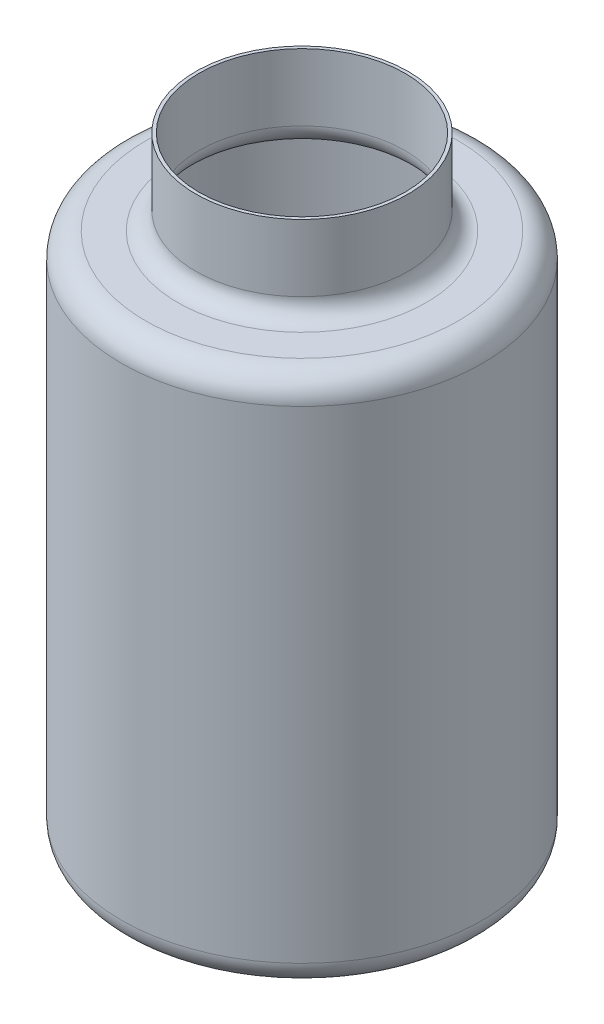
SolidWorks part; units mm, degrees
ref_plane "Front Plane" through (0, 0, 0) normal (0, 0, 1) x (1, 0, 0)
ref_plane "Top Plane" through (0, 0, 0) normal (0, 1, 0) x (1, 0, 0)
ref_plane "Right Plane" through (0, 0, 0) normal (1, 0, 0) x (0, 0, -1)
sketch "Sketch2" plane through (0, 0, 0) normal (0, 0, 1) x (1, 0, 0)
  line L1 (0, 151.638) -> (19.558, 151.638) construction
  line L2 (24.638, 146.558) -> (24.638, 130.556)
  line L3 (29.718, 125.476) -> (37.338, 125.476)
  line L4 (42.418, 120.396) -> (42.418, 5.08)
  line L5 (37.338, 0) -> (0, 0)
  line L6 (0, -97.3781) -> (0, 179.0981) construction
  line L7 (0, 152.4) -> (19.558, 152.4) construction
  line L8 (25.4, 146.558) -> (25.4, 130.556)
  line L9 (29.718, 126.238) -> (37.338, 126.238)
  line L10 (43.18, 120.396) -> (43.18, 5.08)
  line L11 (37.338, -0.762) -> (0, -0.762)
  line L12 (-0.762, 152.4) -> (19.558, 152.4) construction
  line L13 (-0.762, -0.762) -> (-0.762, 152.4) construction
  line L14 (37.338, -0.762) -> (-0.762, -0.762) construction
  line L15 (0, 0) -> (0, 151.638) construction
  line L16 (0, -0.762) -> (0, 0)
  line L17 (0, 152.4) -> (0, 151.638) construction
  line L18 (25.4, 146.558) -> (24.638, 146.558)
  arc A0 (42.418, 5.08) -> (37.338, 0) centre (37.338, 5.08) cw
  arc A1 (37.338, 125.476) -> (42.418, 120.396) centre (37.338, 120.396) cw
  arc A2 (24.638, 130.556) -> (29.718, 125.476) centre (29.718, 130.556) ccw
  arc A3 (19.558, 151.638) -> (24.638, 146.558) centre (19.558, 146.558) cw construction
  arc A4 (19.558, 152.4) -> (25.4, 146.558) centre (19.558, 146.558) cw construction
  arc A5 (25.4, 130.556) -> (29.718, 126.238) centre (29.718, 130.556) ccw
  arc A6 (37.338, 126.238) -> (43.18, 120.396) centre (37.338, 120.396) cw
  arc A7 (43.18, 5.08) -> (37.338, -0.762) centre (37.338, 5.08) cw
  dimension "D1" = 5.08
  dimension "D3" = 25.4
  dimension "D4" = 25.4
  dimension "D5" = 17.78
  dimension "D6" = 127
  dimension "D2" = 0.762
revolve "Revolve1" add sketch "Sketch2" angle 360 about L6
